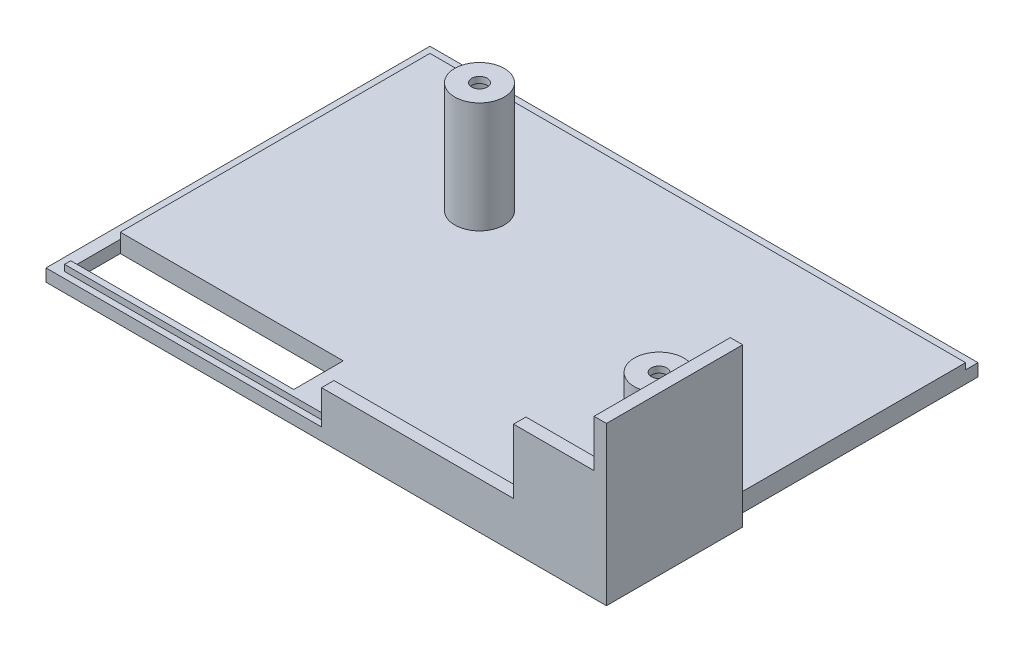
SolidWorks part; units mm, degrees
ref_plane "Front Plane" through (0, 0, 0) normal (0, 0, 1) x (1, 0, 0)
ref_plane "Top Plane" through (0, 0, 0) normal (0, 1, 0) x (1, 0, 0)
ref_plane "Right Plane" through (0, 0, 0) normal (1, 0, 0) x (0, 0, -1)
sketch "Sketch1" plane through (0, 0, 0) normal (0, 1, 0) x (1, 0, 0)
  line L1 (0, 0) -> (90.5, 0)
  line L2 (0, 0) -> (0, 62)
  line L3 (0, 62) -> (90.5, 62)
  line L4 (90.5, 0) -> (90.5, 62)
  dimension "D1" = 90.5
  dimension "D2" = 62
extrude "Boss-Extrude2" add sketch "Sketch1" along normal blind 2
sketch "Sketch5" plane through (0, 2, 0) normal (0, 1, 0) x (1, 0, 0)
  line L0 (90.5, 0) -> (90.5, 62) construction
  line L1 (2, 1) -> (90.5, 1)
  line L2 (2, 1) -> (2, 60)
  line L3 (2, 60) -> (90.5, 60)
  line L4 (90.5, 1) -> (90.5, 60)
  line L5 (0, 62) -> (0, 0) construction
  line L6 (90.5, 62) -> (0, 62) construction
  line L7 (0, 0) -> (90.5, 0) construction
  dimension "D1" = 2
  dimension "D2" = 2
  dimension "D3" = 1
extrude "Boss-Extrude4" add sketch "Sketch5" along normal blind 1
sketch "Sketch6" plane through (0, 2, 0) normal (0, 1, 0) x (1, 0, 0)
  line L1 (44.5, 2) -> (90.5, 2)
  line L2 (44.5, 2) -> (44.5, 0)
  line L3 (44.5, 0) -> (90.5, 0)
  line L4 (90.5, 2) -> (90.5, 0)
  dimension "D1" = 46
  dimension "D2" = 2
extrude "Boss-Extrude5" add sketch "Sketch6" along normal blind 5.5
sketch "Sketch7" plane through (0, 7.5, 0) normal (0, 1, 0) x (1, 0, 0)
  line L0 (90.5, 2) -> (44.5, 2) construction
  line L1 (75.5, 2) -> (90.5, 2)
  line L2 (75.5, 2) -> (75.5, 0)
  line L3 (75.5, 0) -> (90.5, 0)
  line L4 (90.5, 2) -> (90.5, 0)
  dimension "D1" = 15
extrude "Boss-Extrude6" add sketch "Sketch7" along normal blind 10.4
sketch "Sketch8" plane through (0, 3, 0) normal (0, 1, 0) x (1, 0, 0)
  line L1 (88.5, 0) -> (90.5, 0)
  line L2 (88.5, 0) -> (88.5, 22)
  line L3 (88.5, 22) -> (90.5, 22)
  line L4 (90.5, 0) -> (90.5, 22)
  line L5 (90.5, 2) -> (90.5, 60) construction
  line L6 (75.5, 0) -> (90.5, 0) construction
  dimension "D1" = 2
  dimension "D2" = 22
  dimension "D3" = 0
extrude "Boss-Extrude7" add sketch "Sketch8" along normal blind 22.5
sketch "Sketch9" plane through (0, 3, 0) normal (0, 1, 0) x (1, 0, 0)
  line L0 (88.5, 2) -> (44.5, 2) construction
  line L1 (38, 2) -> (2, 2)
  line L2 (38, 2) -> (38, 10)
  line L3 (38, 10) -> (2, 10)
  line L4 (2, 2) -> (2, 10)
  line L5 (2, 60) -> (2, 1) construction
  dimension "D1" = 36
  dimension "D2" = 8
extrude "Cut-Extrude3" cut sketch "Sketch9" against normal blind 15.9
sketch "Sketch10" plane through (0, 3, 0) normal (0, 1, 0) x (1, 0, 0)
  line L0 (90.5, 60) -> (2, 60) construction
  line L1 (2, 60) -> (2, 10) construction
  line L3 (90.5, 60) -> (2, 60) construction
  circle A0 centre (28, 42) radius 4
  circle A1 centre (83, 16) radius 4
  dimension "D3" = 8
  dimension "D6" = 8
  dimension "D1" = 18
  dimension "D2" = 26
  dimension "D4" = 81
  dimension "D5" = 44
extrude "Boss-Extrude9" add sketch "Sketch10" along normal blind 17.9
sketch "Sketch14" plane through (0, 0, 0) normal (0, -1, 0) x (1, 0, 0)
  circle A2 centre (28, -42) radius 3
  circle A3 centre (28, -42) radius 3
  arc A5 (86, -16) -> (86, -16) centre (83, -16) ccw
  circle A6 centre (83, -16) radius 3
  dimension "D1" = 1
  dimension "D2" = 1
extrude "Cut-Extrude7" cut sketch "Sketch14" against normal blind 19.9
sketch "Sketch15" plane through (0, 0, 0) normal (0, -1, 0) x (1, 0, 0)
  circle A0 centre (28, -42) radius 1.25
  circle A1 centre (83, -16) radius 1.25
  dimension "D1" = 2.5
  dimension "D2" = 2.5
extrude "Cut-Extrude8" cut sketch "Sketch15" against normal through all
sketch "Sketch17" plane through (0, 3, 0) normal (0, 1, 0) x (1, 0, 0)
  line L1 (88.5, 22) -> (90.5, 22)
  line L2 (88.5, 22) -> (88.5, 62)
  line L3 (88.5, 62) -> (90.5, 62)
  line L4 (90.5, 22) -> (90.5, 62)
extrude "Cut-Extrude9" cut sketch "Sketch17" against normal through all
